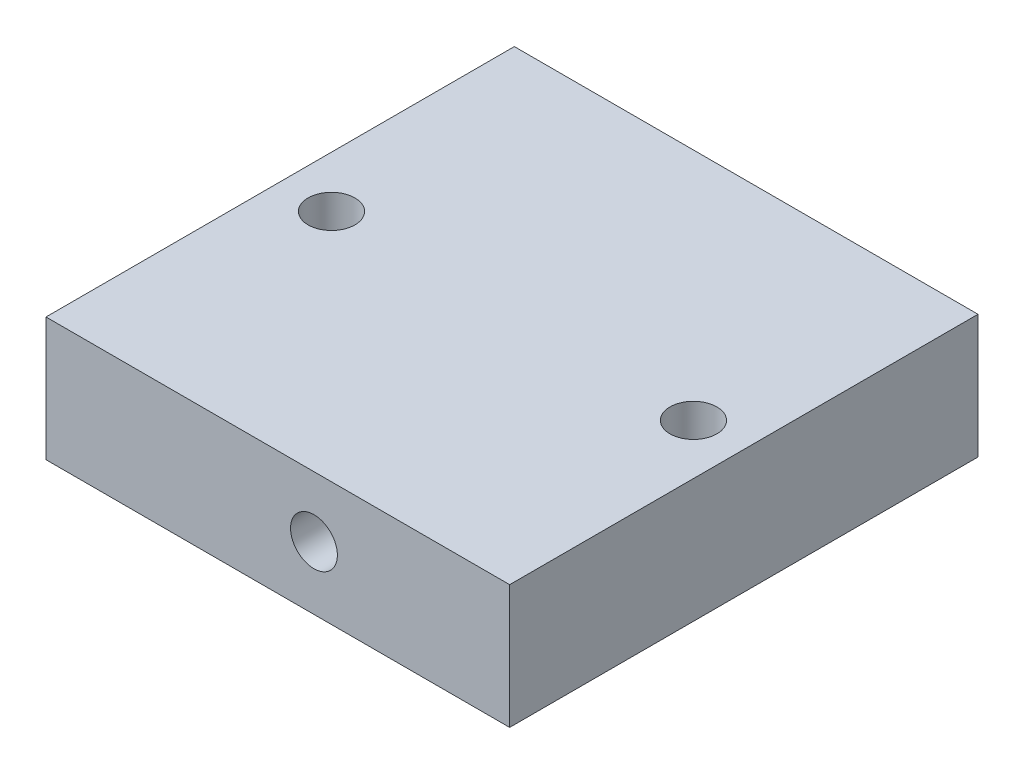
SolidWorks part; units mm, degrees
material "1023 Carbon Steel Sheet (SS)"
ref_plane "Front Plane" through (0, 0, 0) normal (0, 0, 1) x (1, 0, 0)
ref_plane "Top Plane" through (0, 0, 0) normal (0, 1, 0) x (1, 0, 0)
ref_plane "Right Plane" through (0, 0, 0) normal (1, 0, 0) x (0, 0, -1)
sketch "Sketch2" plane through (0, 0, 0) normal (0, 1, 0) x (1, 0, 0)
  line L0 (-224.7039, 0) -> (306.1184, 0) construction
  line L1 (0, 215.7484) -> (0, -186.4391) construction
  line L3 (-247.5, -250) -> (247.5, -250)
  line L4 (-247.5, -250) -> (-247.5, 250)
  line L5 (-247.5, 250) -> (247.5, 250)
  line L6 (247.5, -250) -> (247.5, 250)
  line L7 (-247.5, -250) -> (247.5, 250) construction
  line L8 (-247.5, 250) -> (247.5, -250) construction
  point P5 (0, 0)
  dimension "D1" = 495
  dimension "D2" = 500
extrude "Hips" add sketch "Sketch2" along normal blind 132
sketch "Sketch3" plane through (0, 0, 250) normal (0, 0, 1) x (1, 0, 0)
  circle A0 centre (38.5869, 67.2852) radius 25
  dimension "D1" = 50
extrude "Femur-hole" cut sketch "Sketch3" against normal through all
sketch "Sketch4" plane through (0, 0, 0) normal (0, -1, 0) x (1, 0, 0)
  circle A0 centre (193.718, 0) radius 25
  dimension "D1" = 50
extrude "Tail-hole" cut sketch "Sketch4" against normal through all
sketch "Sketch5" plane through (0, 0, 0) normal (0, -1, 0) x (1, 0, 0)
  circle A0 centre (-192.6981, 0) radius 25
  dimension "D1" = 50
extrude "Neck-hole" cut sketch "Sketch5" against normal through all
